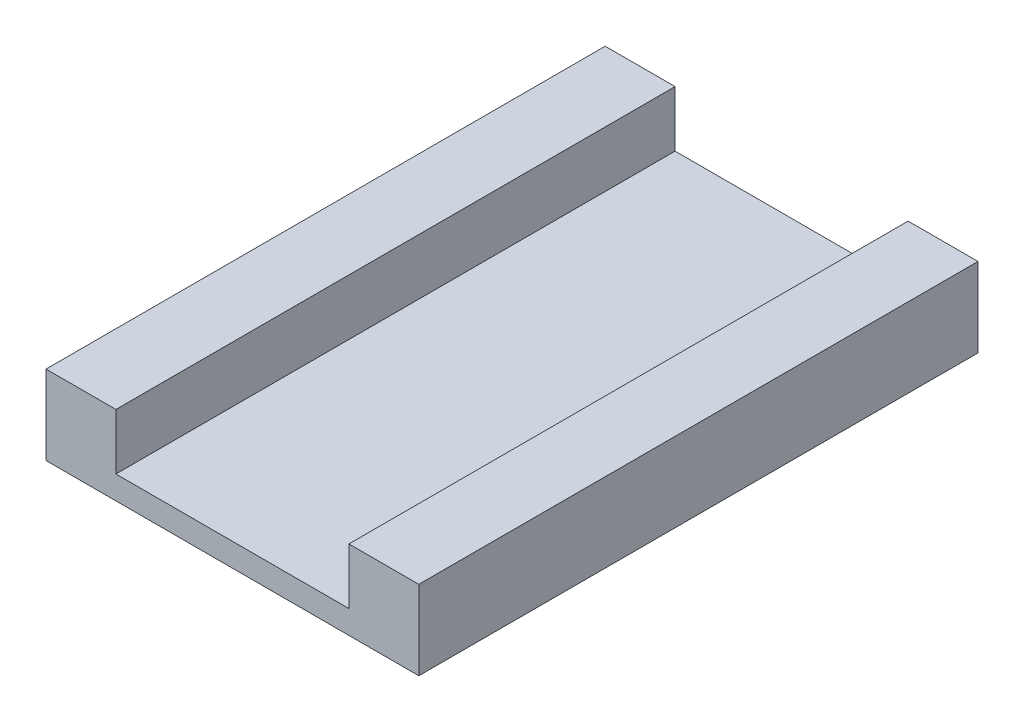
SolidWorks part; units mm, degrees
ref_plane "Front Plane" through (0, 0, 0) normal (0, 0, 1) x (1, 0, 0)
ref_plane "Top Plane" through (0, 0, 0) normal (0, 1, 0) x (1, 0, 0)
ref_plane "Right Plane" through (0, 0, 0) normal (1, 0, 0) x (0, 0, -1)
sketch "Sketch1" plane through (0, 0, 0) normal (0, 1, 0) x (1, 0, 0)
  line L1 (0, 0) -> (40, 0)
  line L2 (0, 0) -> (0, 60)
  line L3 (0, 60) -> (40, 60)
  line L4 (40, 0) -> (40, 60)
  dimension "D1" = 60
  dimension "D2" = 40
extrude "Boss-Extrude1" add sketch "Sketch1" along normal blind 8.5
sketch "Sketch2" plane through (0, 8.5, 0) normal (0, 1, 0) x (1, 0, 0)
  line L0 (40, 60) -> (0, 60) construction
  line L1 (7.5, 60) -> (32.5, 60)
  line L2 (7.5, 60) -> (7.5, 0)
  line L3 (7.5, 0) -> (32.5, 0)
  line L4 (32.5, 60) -> (32.5, 0)
  line L5 (0, 0) -> (40, 0) construction
  line L6 (0, 21.6774) -> (7.5, 21.6774) construction
  line L7 (0, 60) -> (0, 0) construction
  line L8 (32.5, 21.6774) -> (40, 21.6774) construction
  line L9 (40, 0) -> (40, 60) construction
  dimension "D1" = 25
extrude "Cut-Extrude1" cut sketch "Sketch2" against normal blind 6
